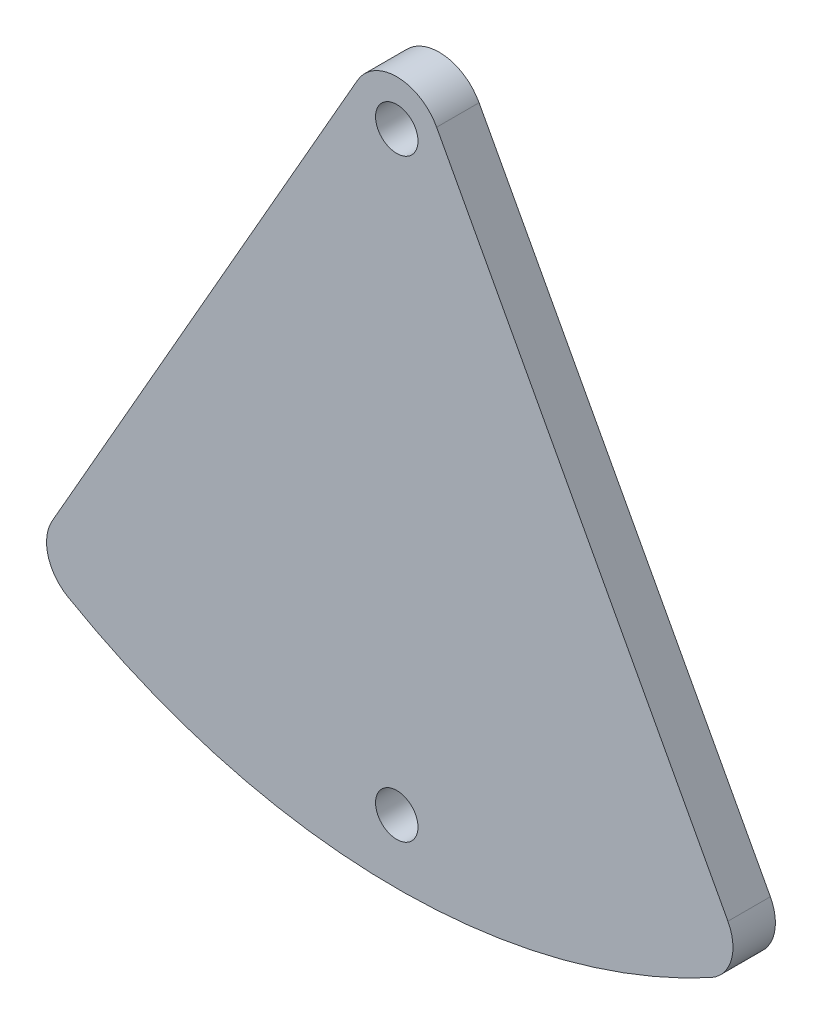
SolidWorks part; units mm, degrees
ref_plane "Plane1" through (0, 0, 0) normal (0, 0, 1) x (1, 0, 0)
ref_plane "Plane2" through (0, 0, 0) normal (0, 1, 0) x (1, 0, 0)
ref_plane "Plane3" through (0, 0, 0) normal (1, 0, 0) x (0, 0, -1)
other "Configuration Table"
sketch "Sketch1" plane through (0, 0, 0) normal (0, 0, 1) x (1, 0, 0)
  line L0 (9.3977, 105.0506) -> (78.0392, -22.6714)
  line L1 (-9.263, 105.2935) -> (-81.2058, -20.5985)
  arc A0 (9.3977, 105.0506) -> (-9.263, 105.2935) centre (0, 100) ccw
  circle A1 centre (0, -40) radius 5
  arc A2 (-77.5251, -34.2194) -> (74.0052, -36.1919) centre (0, 100) ccw
  circle A3 centre (0, 100) radius 5
  arc A4 (78.0392, -22.6714) -> (74.0052, -36.1919) centre (69.2307, -27.4053) cw
  arc A5 (-81.2058, -20.5985) -> (-77.5251, -34.2194) centre (-72.5235, -25.5601) ccw
  dimension "D1" = 10
  dimension "D2" = 10
  dimension "D3" = 155
  dimension "D4" = 10
extrude "Base-Extrude" add sketch "Sketch1" along normal mid plane 10
